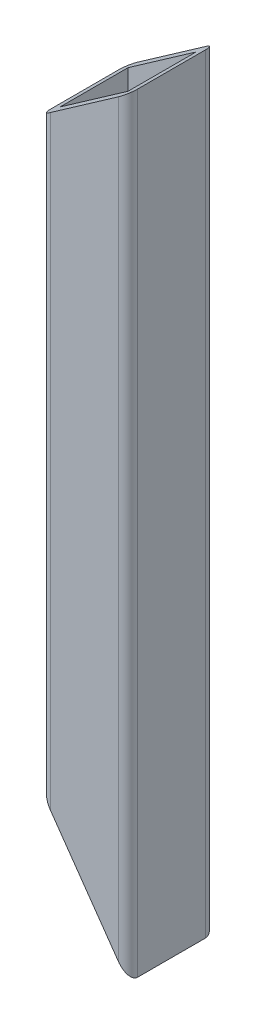
SolidWorks part; units mm, degrees
material "Plain Carbon Steel"
ref_plane "Front Plane" through (0, 0, 0) normal (0, 0, 1) x (1, 0, 0)
ref_plane "Top Plane" through (0, 0, 0) normal (0, 1, 0) x (1, 0, 0)
ref_plane "Right Plane" through (0, 0, 0) normal (1, 0, 0) x (0, 0, -1)
sketch "Sketch1" plane through (0, 0, 0) normal (0, 1, 0) x (1, 0, 0)
  line L1 (2.8, 0) -> (22.8, 0)
  line L2 (0, -2.8) -> (0, -22.8)
  line L3 (2.8, -25.6) -> (22.8, -25.6)
  line L4 (25.6, -2.8) -> (25.6, -22.8)
  arc A0 (22.8, 0) -> (25.6, -2.8) centre (22.8, -2.8) cw
  arc A1 (22.8, -25.6) -> (25.6, -22.8) centre (22.8, -22.8) ccw
  arc A2 (0, -22.8) -> (2.8, -25.6) centre (2.8, -22.8) ccw
  arc A3 (2.8, 0) -> (0, -2.8) centre (2.8, -2.8) ccw
  point P7 (25.6, 0)
  point P10 (25.6, -25.6)
  point P15 (0, 0)
  dimension "D2" = 2.8
  dimension "D1" = 25.6
extrude "Boss-Extrude1" add sketch "Sketch1" along normal blind 226
sketch "Sketch3" plane through (0, 0, 0) normal (0, -1, 0) x (-1, 0, 0)
  line L4 (-2.8, -2.8) -> (-22.8, -2.8)
  line L5 (-2.8, -2.8) -> (-2.8, -22.8)
  line L6 (-2.8, -22.8) -> (-22.8, -22.8)
  line L7 (-22.8, -2.8) -> (-22.8, -22.8)
  line L8 (-2.8, -2.8) -> (-22.8, -22.8) construction
  line L9 (-2.8, -22.8) -> (-22.8, -2.8) construction
  point P6 (-12.8, -12.8)
extrude "Cut-Extrude1" cut sketch "Sketch3" against normal blind 226
sketch "Sketch4" plane through (0, 0, 25.6) normal (0, 0, 1) x (1, 0, 0)
  line L0 (25.7948, 0) -> (0, 36.8019)
extrude "Cut-Extrude2" cut sketch "Sketch4" against normal through all and the other way through all
sketch "Sketch5" plane through (0, 0, 25.6) normal (0, 0, 1) x (1, 0, 0)
  line L0 (25.6, 226) -> (0, 208.0747)
  line L1 (0, 226) -> (0, 36.8019) construction
extrude "Cut-Extrude6" cut sketch "Sketch5" against normal through all and the other way through all flip side to cut
